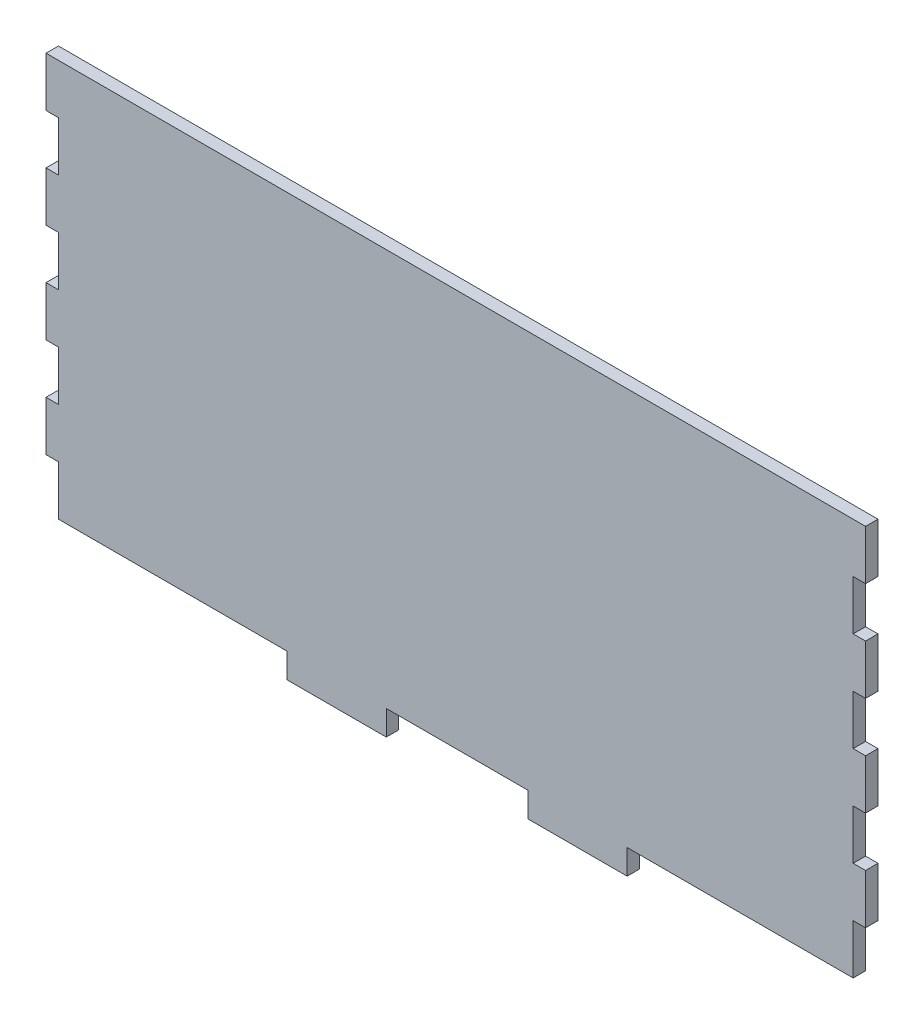
SolidWorks part; units mm, degrees
ref_plane "Front Plane" through (0, 0, 0) normal (0, 0, 1) x (1, 0, 0)
ref_plane "Top Plane" through (0, 0, 0) normal (0, 1, 0) x (1, 0, 0)
ref_plane "Right Plane" through (0, 0, 0) normal (1, 0, 0) x (0, 0, -1)
sketch "Sketch1" plane through (0, 0, 0) normal (0, 0, 1) x (1, 0, 0)
  line L1 (-101.6, -50.8) -> (101.6, -50.8)
  line L2 (-101.6, -50.8) -> (-101.6, 50.8)
  line L3 (-101.6, 50.8) -> (101.6, 50.8)
  line L4 (101.6, -50.8) -> (101.6, 50.8)
  line L5 (-101.6, -50.8) -> (101.6, 50.8) construction
  line L6 (-101.6, 50.8) -> (101.6, -50.8) construction
  point P0 (0, 0)
  dimension "D1" = 203.2
  dimension "D2" = 101.6
extrude "Boss-Extrude1" add sketch "Sketch1" along normal blind 3.175
sketch "Sketch2" plane through (0, 0, 3.175) normal (0, 0, 1) x (1, 0, 0)
  line L0 (-101.6, 25.4) -> (-104.775, 25.4)
  line L1 (-101.6, 50.8) -> (-104.775, 50.8)
  line L2 (-101.6, 50.8) -> (-101.6, 38.1)
  line L3 (-101.6, 38.1) -> (-104.775, 38.1)
  line L4 (-104.775, 50.8) -> (-104.775, 38.1)
  line L5 (-101.6, 25.4) -> (-101.6, 12.7)
  line L6 (-101.6, 12.7) -> (-104.775, 12.7)
  line L7 (-104.775, 25.4) -> (-104.775, 12.7)
  line L8 (-101.6, 0) -> (-104.775, 0)
  line L9 (-101.6, 0) -> (-101.6, -12.7)
  line L10 (-101.6, -12.7) -> (-104.775, -12.7)
  line L11 (-104.775, 0) -> (-104.775, -12.7)
  line L12 (-101.6, -25.4) -> (-104.775, -25.4)
  line L13 (-101.6, -25.4) -> (-101.6, -38.1)
  line L14 (-101.6, -38.1) -> (-104.775, -38.1)
  line L15 (-104.775, -25.4) -> (-104.775, -38.1)
  line L16 (-101.6, -50.8) -> (101.6, -50.8) construction
  line L17 (-79.375, -50.8) -> (-104.775, -50.8)
  line L18 (-79.375, -50.8) -> (-79.375, -57.15)
  line L19 (-79.375, -57.15) -> (-104.775, -57.15)
  line L20 (-104.775, -50.8) -> (-104.775, -57.15)
  line L21 (-17.78, -50.8) -> (-43.18, -50.8)
  line L22 (-17.78, -50.8) -> (-17.78, -57.15)
  line L23 (-17.78, -57.15) -> (-43.18, -57.15)
  line L24 (-43.18, -50.8) -> (-43.18, -57.15)
  line L25 (43.815, -50.8) -> (18.415, -50.8)
  line L26 (43.815, -50.8) -> (43.815, -57.15)
  line L27 (43.815, -57.15) -> (18.415, -57.15)
  line L28 (18.415, -50.8) -> (18.415, -57.15)
  line L29 (105.41, -50.8) -> (80.01, -50.8)
  line L30 (105.41, -50.8) -> (105.41, -57.15)
  line L31 (105.41, -57.15) -> (80.01, -57.15)
  line L32 (80.01, -50.8) -> (80.01, -57.15)
  line L33 (101.6, -50.8) -> (101.6, 50.8) construction
  line L34 (0, 0) -> (0, 50.8) construction
  line L35 (101.6, 50.8) -> (-101.6, 50.8) construction
  line L36 (104.775, -25.4) -> (104.775, -38.1)
  line L37 (101.6, -38.1) -> (104.775, -38.1)
  line L38 (101.6, -25.4) -> (101.6, -38.1)
  line L39 (101.6, -25.4) -> (104.775, -25.4)
  line L40 (104.775, 0) -> (104.775, -12.7)
  line L41 (101.6, -12.7) -> (104.775, -12.7)
  line L42 (101.6, 0) -> (101.6, -12.7)
  line L43 (101.6, 0) -> (104.775, 0)
  line L44 (104.775, 25.4) -> (104.775, 12.7)
  line L45 (101.6, 12.7) -> (104.775, 12.7)
  line L46 (101.6, 25.4) -> (101.6, 12.7)
  line L47 (104.775, 50.8) -> (104.775, 38.1)
  line L48 (101.6, 38.1) -> (104.775, 38.1)
  line L49 (101.6, 50.8) -> (101.6, 38.1)
  line L50 (101.6, 50.8) -> (104.775, 50.8)
  line L51 (101.6, 25.4) -> (104.775, 25.4)
  dimension "D1" = 3.175
  dimension "D2" = 12.7
  dimension "D4" = 6.35
  dimension "D5" = 25.4
  dimension "D7" = 61.595
  dimension "D8" = 3.81
  dimension "D3" = 4
  dimension "D6" = 4
extrude "Boss-Extrude2" add sketch "Sketch2" against normal blind 3.175
sketch "Sketch3" plane through (0, 0, 3.175) normal (0, 0, 1) x (1, 0, 0)
  line L1 (-79.375, -50.8) -> (-104.775, -50.8)
  line L2 (-79.375, -50.8) -> (-79.375, -57.15)
  line L3 (-79.375, -57.15) -> (-104.775, -57.15)
  line L4 (-104.775, -50.8) -> (-104.775, -57.15)
  line L5 (80.01, -50.8) -> (105.41, -50.8)
  line L6 (80.01, -50.8) -> (80.01, -57.15)
  line L7 (80.01, -57.15) -> (105.41, -57.15)
  line L8 (105.41, -50.8) -> (105.41, -57.15)
extrude "Cut-Extrude1" cut sketch "Sketch3" against normal through all
